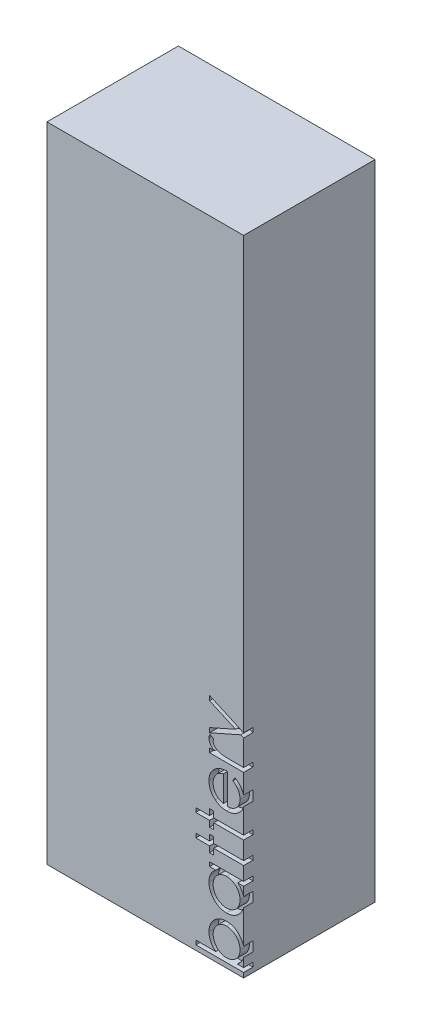
SolidWorks part; units mm, degrees
ref_plane "前视基准面" through (0, 0, 0) normal (0, 0, 1) x (1, 0, 0)
ref_plane "上视基准面" through (0, 0, 0) normal (0, 1, 0) x (1, 0, 0)
ref_plane "右视基准面" through (0, 0, 0) normal (1, 0, 0) x (0, 0, -1)
sketch "草图1" plane through (0, 0, 0) normal (0, 0, 1) x (1, 0, 0)
  line L1 (0, 0) -> (42.2, 0)
  line L2 (0, 0) -> (0, -138)
  line L3 (0, -138) -> (42.2, -138)
  line L4 (42.2, 0) -> (42.2, -138)
  dimension "D1" = 42.2
  dimension "D2" = 138
extrude "凸台-拉伸1" add sketch "草图1" along normal blind 28.2
sketch "草图2" plane through (0, 0, 28.2) normal (0, 0, 1) x (1, 0, 0)
  text T0 "battery" font "Century Gothic" height 10
extrude "切除-拉伸1" cut sketch "草图2" against normal blind 2
